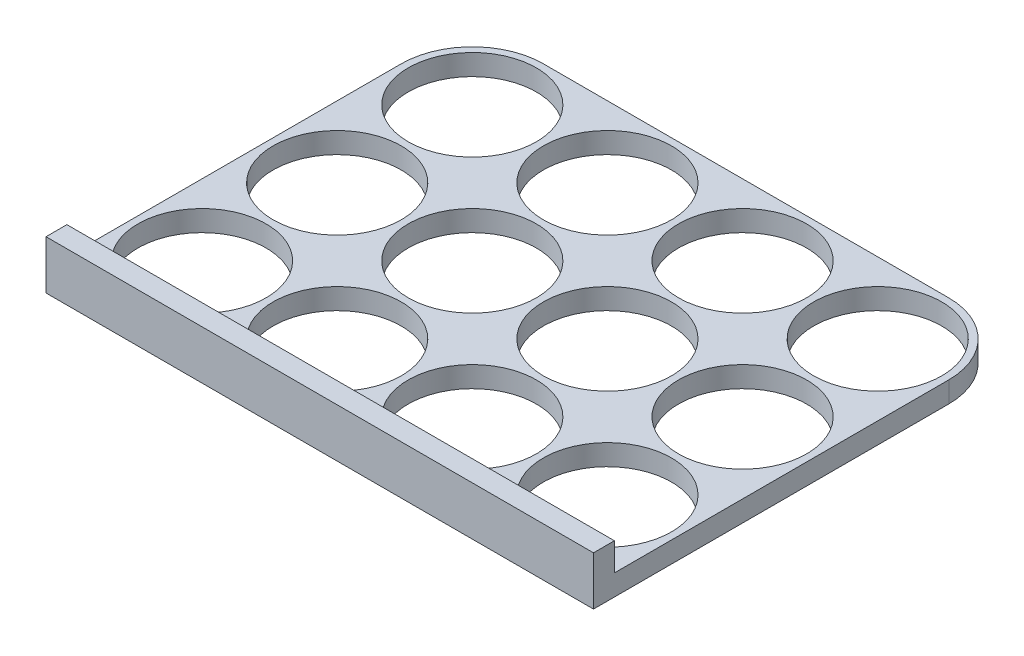
SolidWorks part; units mm, degrees
ref_plane "Front Plane" through (0, 0, 0) normal (0, 0, 1) x (1, 0, 0)
ref_plane "Top Plane" through (0, 0, 0) normal (0, 1, 0) x (1, 0, 0)
ref_plane "Right Plane" through (0, 0, 0) normal (1, 0, 0) x (0, 0, -1)
sketch "Sketch1" plane through (0, 0, 0) normal (0, 1, 0) x (1, 0, 0)
  line L0 (0, 48) -> (58.2, 48) construction
  line L1 (67.4, 38.8) -> (67.4, 0) construction
  line L2 (-9.2, 38.8) -> (-9.2, 0) construction
  line L3 (0, 49) -> (58.2, 49)
  line L4 (-10.2, 38.8) -> (-10.2, 0)
  line L5 (68.4, 38.8) -> (68.4, 0)
  line L6 (-10.2, 0) -> (-10.2, -12.2)
  line L7 (-10.2, -12.2) -> (68.4, -12.2)
  line L8 (68.4, -12.2) -> (68.4, 0)
  line L9 (0, -9.2) -> (58.2, -9.2) construction
  circle A0 centre (0, 0) radius 9.2
  circle A1 centre (19.4, 0) radius 9.2
  circle A2 centre (38.8, 0) radius 9.2
  circle A3 centre (58.2, 0) radius 9.2
  circle A4 centre (19.4, 19.4) radius 9.2
  circle A5 centre (38.8, 19.4) radius 9.2
  circle A6 centre (58.2, 19.4) radius 9.2
  circle A7 centre (19.4, 38.8) radius 9.2
  circle A8 centre (38.8, 38.8) radius 9.2
  circle A9 centre (58.2, 38.8) radius 9.2
  circle A10 centre (0, 19.4) radius 9.2
  circle A11 centre (0, 38.8) radius 9.2
  arc A12 (-10.2, 38.8) -> (0, 49) centre (0, 38.8) cw
  arc A13 (58.2, 49) -> (68.4, 38.8) centre (58.2, 38.8) cw
  point P33 (29.1, 48)
  dimension "D1" = 18.4
  dimension "D4" = 1
  dimension "D5" = 1
  dimension "D6" = 1
  dimension "D7" = 19.4
  dimension "D8" = 19.4
  dimension "D9" = 3
  dimension "D2" = 4
  dimension "D3" = 3
extrude "Boss-Extrude1" add sketch "Sketch1" along normal blind 3
sketch "Sketch2" plane through (0, 3, 0) normal (0, 1, 0) x (1, 0, 0)
  line L0 (68.4, -12.2) -> (68.4, 38.8) construction
  line L1 (-10.2, -12.2) -> (68.4, -12.2)
  line L2 (-10.2, -12.2) -> (-10.2, -9.2)
  line L3 (-10.2, -9.2) -> (68.4, -9.2)
  line L4 (68.4, -12.2) -> (68.4, -9.2)
  dimension "D1" = 3
extrude "Boss-Extrude2" add sketch "Sketch2" along normal blind 4
